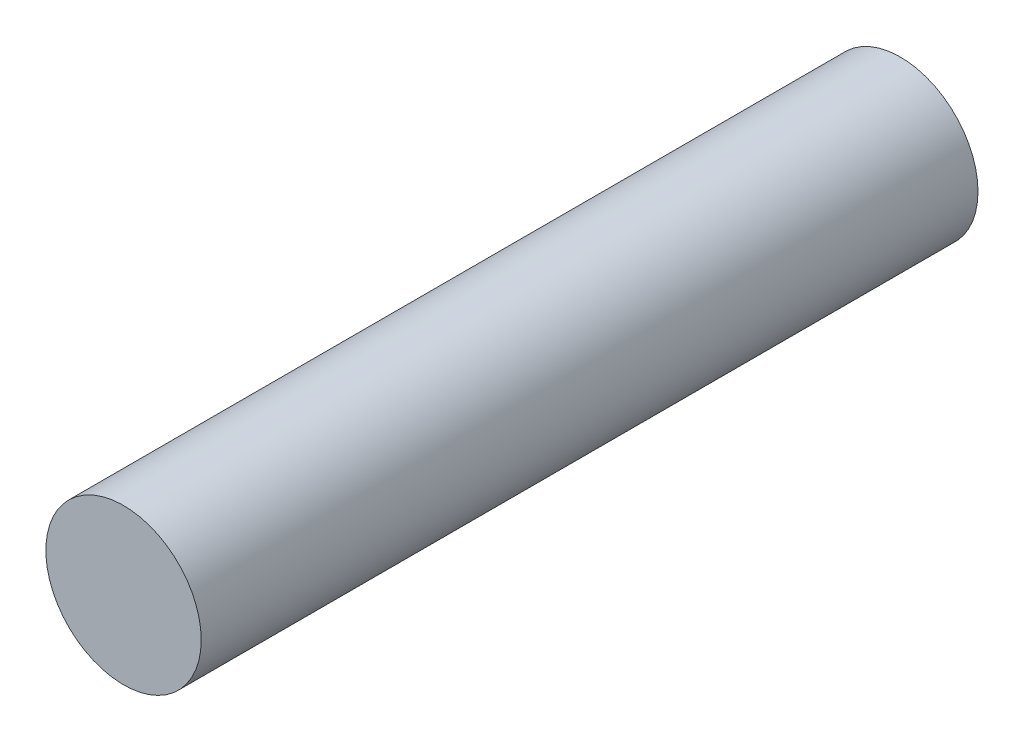
SolidWorks part; units mm, degrees
material "Plain Carbon Steel"
ref_plane "Front Plane" through (0, 0, 0) normal (0, 0, 1) x (1, 0, 0)
ref_plane "Top Plane" through (0, 0, 0) normal (0, 1, 0) x (1, 0, 0)
ref_plane "Right Plane" through (0, 0, 0) normal (1, 0, 0) x (0, 0, -1)
sketch "Sketch1" plane through (0, 0, 0) normal (0, 0, 1) x (1, 0, 0)
  circle A0 centre (0, 0) radius 5
  dimension "D1" = 10
extrude "Boss-Extrude1" add sketch "Sketch1" along normal mid plane 50
